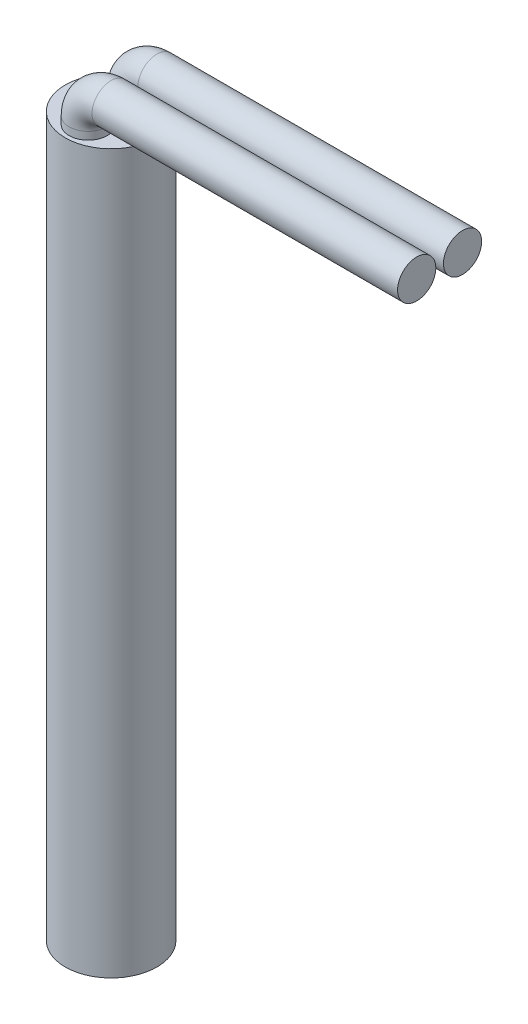
SolidWorks part; units mm, degrees
ref_plane "Front Plane" through (0, 0, 0) normal (0, 0, 1) x (1, 0, 0)
ref_plane "Top Plane" through (0, 0, 0) normal (0, 1, 0) x (1, 0, 0)
ref_plane "Right Plane" through (0, 0, 0) normal (1, 0, 0) x (0, 0, -1)
sketch "Sketch1" plane through (0, 0, 0) normal (0, 1, 0) x (1, 0, 0)
  circle A0 centre (0, 0) radius 3
  dimension "D1" = 6
extrude "Boss-Extrude1" add sketch "Sketch1" along normal blind 47
ref_plane "Plane1" through (0, 0, 1.5) normal (0, 0, 1) x (1, 0, 0)
sketch "Sketch2" plane through (0, 0, 1.5) normal (0, 0, 1) x (1, 0, 0)
  line L0 (0, 47) -> (0, 47.5)
  line L1 (3, 47) -> (-3, 47) construction
  line L2 (1.5, 49) -> (21.5, 49)
  arc A0 (0, 47.5) -> (1.5, 49) centre (1.5, 47.5) cw
  dimension "D1" = 1.5
  dimension "D2" = 0.5
  dimension "D3" = 20
sketch "Sketch3" plane through (0, 47, 0) normal (0, 1, 0) x (1, 0, 0)
  line L0 (0, -1.5) -> (1.5, -1.5) construction
  circle A0 centre (0, -1.5) radius 1.25
  point P4 (0, 0)
  dimension "D1" = 2.5
sweep "Sweep1" add profiles "Sketch3" path "Sketch2"
mirror "Mirror1" about plane through (0, 0, 0) normal (0, 0, 1) of "Sweep1"
